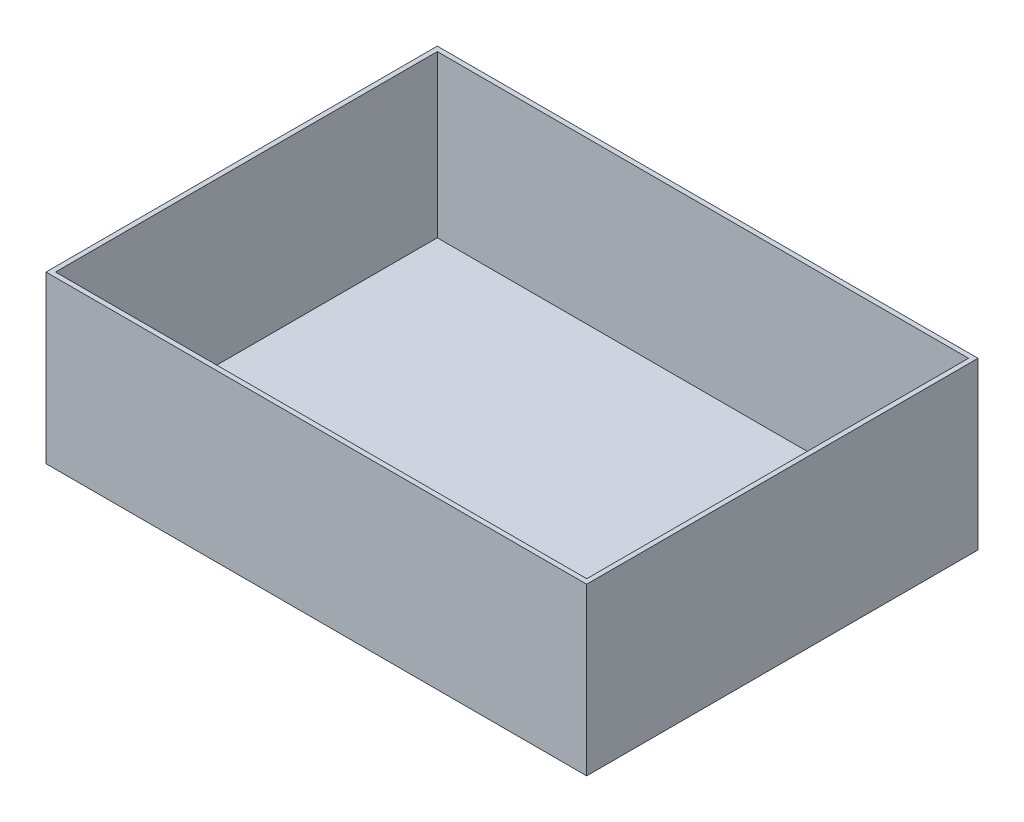
SolidWorks part; units mm, degrees
material "Polyether Polyol"
ref_plane "Frontal Plane" through (0, 0, 0) normal (0, 0, 1) x (1, 0, 0)
ref_plane "Horizontal Plane" through (0, 0, 0) normal (0, 1, 0) x (1, 0, 0)
ref_plane "Profile Plane" through (0, 0, 0) normal (1, 0, 0) x (0, 0, -1)
sketch "Sketch1" plane through (0, 0, 0) normal (0, 1, 0) x (1, 0, 0)
  line L1 (-96.7437, 78.2646) -> (131.2563, 78.2646)
  line L2 (-96.7437, 78.2646) -> (-96.7437, -86.7354)
  line L3 (-96.7437, -86.7354) -> (131.2563, -86.7354)
  line L4 (131.2563, 78.2646) -> (131.2563, -86.7354)
  dimension "D1" = 228
  dimension "D2" = 165
extrude "Boss-Extrude1" add sketch "Sketch1" along normal blind 70
sketch "Sketch2" plane through (0, 70, 0) normal (0, 1, 0) x (1, 0, 0)
  line L4 (-94.7437, 76.2646) -> (-94.7437, -84.7354)
  line L5 (-96.7437, 78.2646) -> (131.2563, 78.2646)
  line L6 (-96.7437, 78.2646) -> (-96.7437, -86.7354)
  line L7 (-96.7437, -86.7354) -> (131.2563, -86.7354)
  line L8 (131.2563, 78.2646) -> (131.2563, -86.7354)
  line L9 (-94.7437, -84.7354) -> (129.2563, -84.7354)
  line L10 (129.2563, 76.2646) -> (129.2563, -84.7354)
  line L11 (-94.7437, 76.2646) -> (129.2563, 76.2646)
  dimension "D1" = 2
extrude "Cut-Extrude1" cut sketch "Sketch2" against normal blind 68 flip side to cut
